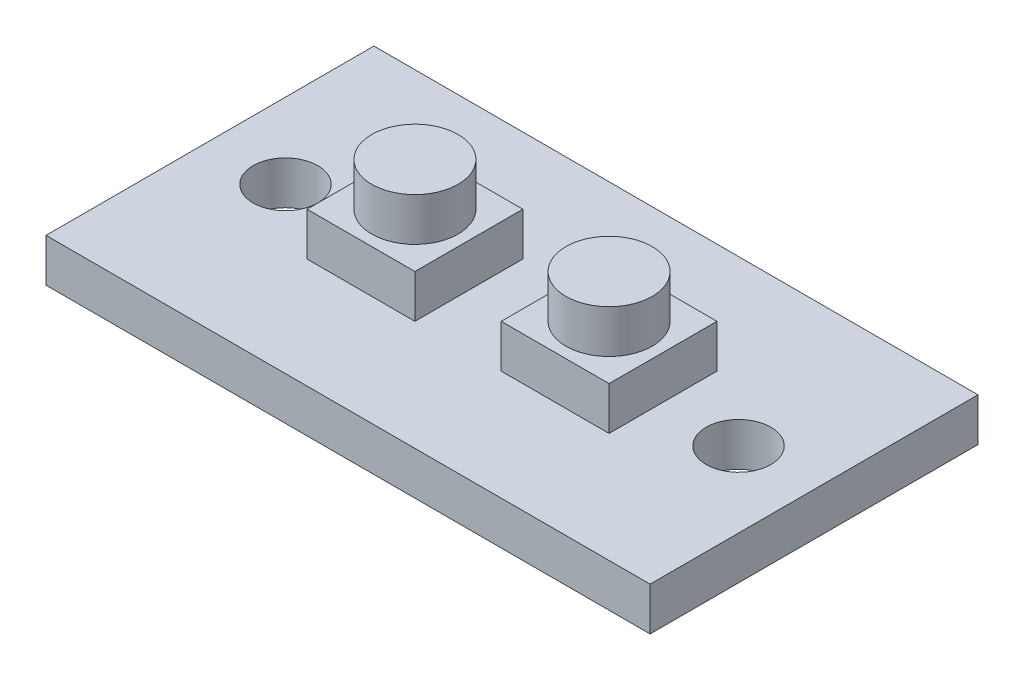
SolidWorks part; units mm, degrees
ref_plane "前视基准面" through (0, 0, 0) normal (0, 0, 1) x (1, 0, 0)
ref_plane "上视基准面" through (0, 0, 0) normal (0, 1, 0) x (1, 0, 0)
ref_plane "右视基准面" through (0, 0, 0) normal (1, 0, 0) x (0, 0, -1)
other "Configuration Table"
sketch "草图1" plane through (0, 0, 0) normal (0, 1, 0) x (1, 0, 0)
  line L1 (-14, -7.6) -> (14, -7.6)
  line L2 (-14, -7.6) -> (-14, 7.6)
  line L3 (-14, 7.6) -> (14, 7.6)
  line L4 (14, -7.6) -> (14, 7.6)
  line L5 (-14, -7.6) -> (14, 7.6) construction
  line L6 (-14, 7.6) -> (14, -7.6) construction
  circle A0 centre (10.5, 0) radius 1.5
  circle A1 centre (-10.5, 0) radius 1.5
  point P0 (0, 0)
  dimension "D3" = 3
  dimension "D4" = 3
  dimension "D5" = 3.5
  dimension "D6" = 3.5
  dimension "D1" = 28
  dimension "D2" = 15.2
extrude "凸台-拉伸1" add sketch "草图1" along normal blind 2
sketch "草图2" plane through (0, 2, 0) normal (0, 1, 0) x (1, 0, 0)
  line L0 (0, 9.9521) -> (0, -13.2082) construction
  line L1 (2, -2.5) -> (7, -2.5)
  line L2 (2, -2.5) -> (2, 2.5)
  line L3 (2, 2.5) -> (7, 2.5)
  line L4 (7, -2.5) -> (7, 2.5)
  line L5 (2, -2.5) -> (7, 2.5) construction
  line L6 (2, 2.5) -> (7, -2.5) construction
  line L7 (-2, 2.5) -> (-7, -2.5) construction
  line L8 (-2, -2.5) -> (-7, 2.5) construction
  line L9 (-7, -2.5) -> (-7, 2.5)
  line L10 (-2, 2.5) -> (-7, 2.5)
  line L11 (-2, -2.5) -> (-2, 2.5)
  line L12 (-2, -2.5) -> (-7, -2.5)
  point P0 (4.5, 0)
  point P8 (0, 0)
  point P13 (-4.5, 0)
  dimension "D1" = 2
  dimension "D2" = 5
  dimension "D3" = 5
extrude "凸台-拉伸2" add sketch "草图2" along normal blind 2
sketch "草图3" plane through (0, 4, 0) normal (0, 1, 0) x (1, 0, 0)
  line L0 (2, 2.5) -> (7, -2.5) construction
  line L1 (0, 5.4366) -> (0, -8.7398) construction
  line L2 (-2, 2.5) -> (-7, -2.5) construction
  circle A0 centre (4.5, 0) radius 2
  circle A1 centre (-4.5, 0) radius 2
  dimension "D1" = 4
extrude "凸台-拉伸3" add sketch "草图3" along normal blind 2
